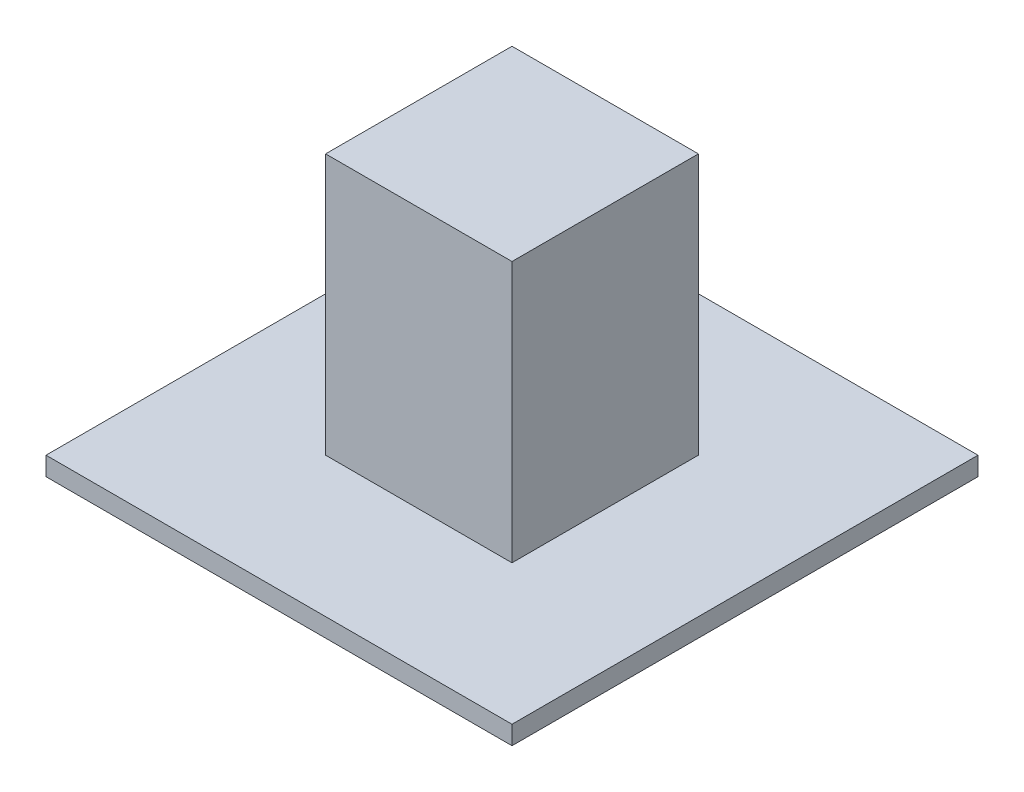
SolidWorks part; units mm, degrees
ref_plane "Front Plane" through (0, 0, 0) normal (0, 0, 1) x (1, 0, 0)
ref_plane "Top Plane" through (0, 0, 0) normal (0, 1, 0) x (1, 0, 0)
ref_plane "Right Plane" through (0, 0, 0) normal (1, 0, 0) x (0, 0, -1)
sketch "Sketch1" plane through (0, 0, 0) normal (0, 1, 0) x (1, 0, 0)
  line L1 (-1, -1) -> (1, -1)
  line L2 (-1, -1) -> (-1, 1)
  line L3 (-1, 1) -> (1, 1)
  line L4 (1, -1) -> (1, 1)
  line L5 (-1, -1) -> (1, 1) construction
  line L6 (-1, 1) -> (1, -1) construction
  point P0 (0, 0)
  dimension "D1" = 2
  dimension "D2" = 2
extrude "Boss-Extrude1" add sketch "Sketch1" along normal blind 2.8
sketch "Sketch2" plane through (0, 0, 0) normal (0, 1, 0) x (1, 0, 0)
  line L1 (-2.5, -2.5) -> (2.5, -2.5)
  line L2 (-2.5, -2.5) -> (-2.5, 2.5)
  line L3 (-2.5, 2.5) -> (2.5, 2.5)
  line L4 (2.5, -2.5) -> (2.5, 2.5)
  line L5 (-2.5, -2.5) -> (2.5, 2.5) construction
  line L6 (-2.5, 2.5) -> (2.5, -2.5) construction
  point P0 (0, 0)
  dimension "D1" = 5
  dimension "D2" = 5
extrude "Boss-Extrude2" add sketch "Sketch2" against normal blind 0.2
sketch "Sketch3" plane through (0, -0.2, 0) normal (0, -1, 0) x (-1, 0, 0)
  line L0 (-2.5, 0) -> (2.5, 0) construction
  line L1 (-2.5, -2.5) -> (-2.5, 2.5) construction
  line L2 (2.5, 2.5) -> (2.5, -2.5) construction
  line L3 (0, 2.5) -> (0, -2.5) construction
  line L4 (-2.5, 2.5) -> (2.5, 2.5) construction
  line L5 (2.5, -2.5) -> (-2.5, -2.5) construction
  circle A0 centre (0, 0) radius 0.5
  point P14 (0, 0)
  dimension "D1" = 1
extrude "Boss-Extrude3" add sketch "Sketch3" along normal blind 1
scale "Scale1" scale about centroid uniform scaling yes scale factor 6
